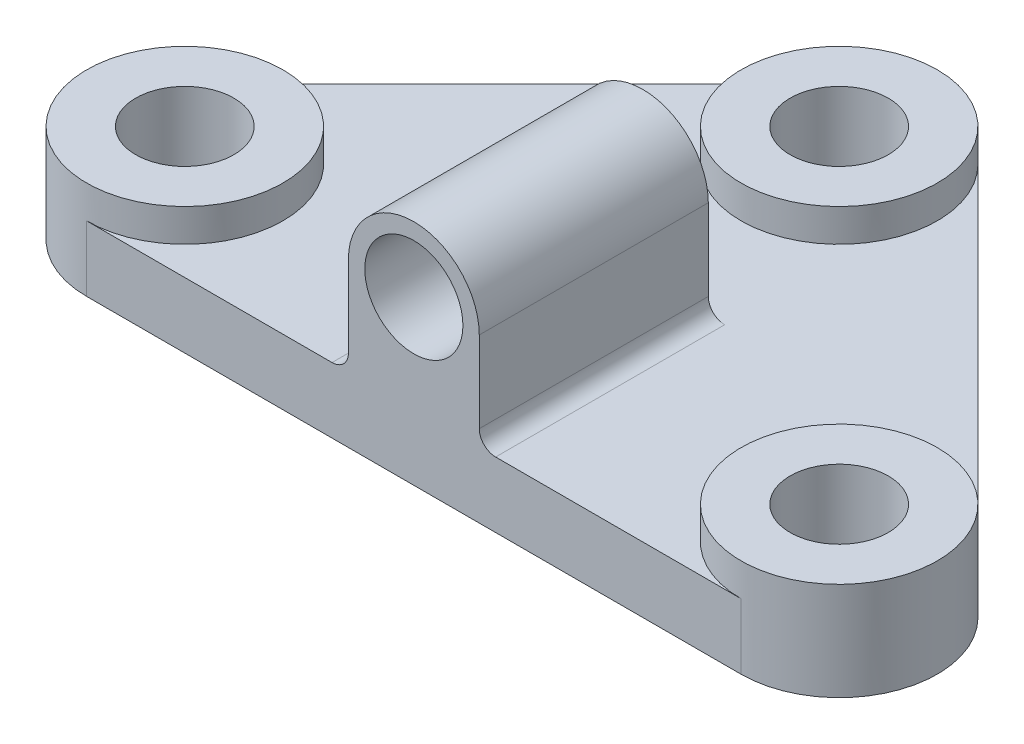
SolidWorks part; units mm, degrees
ref_plane "Front Plane" through (0, 0, 0) normal (0, 0, 1) x (1, 0, 0)
ref_plane "Top Plane" through (0, 0, 0) normal (0, 1, 0) x (1, 0, 0)
ref_plane "Right Plane" through (0, 0, 0) normal (1, 0, 0) x (0, 0, -1)
sketch "Sketch1" plane through (0, 0, 0) normal (0, 1, 0) x (1, 0, 0)
  line L0 (-100, 0) -> (100, 0) construction
  line L4 (-100, 0) -> (0, 100) construction
  line L5 (0, 100) -> (100, 0) construction
  line L6 (-121.2132, 21.2132) -> (-21.2132, 121.2132)
  line L7 (-100, -30) -> (100, -30)
  line L8 (21.2132, 121.2132) -> (121.2132, 21.2132)
  arc A1 (-21.2132, 121.2132) -> (21.2132, 121.2132) centre (0, 100) ccw
  arc A2 (-100, -30) -> (-121.2132, 21.2132) centre (-100, 0) ccw
  arc A3 (121.2132, 21.2132) -> (100, -30) centre (100, 0) ccw
  circle A4 centre (0, 100) radius 15
  circle A5 centre (-100, 0) radius 15
  circle A6 centre (100, 0) radius 15
  point P1 (0, 0)
  point P11 (0, 0)
  dimension "D3" = 60
  dimension "D4" = 60
  dimension "D5" = 60
  dimension "D6" = 30
  dimension "D7" = 30
  dimension "D8" = 30
  dimension "D1" = 200
  dimension "D2" = 100
extrude "Boss-Extrude2" add sketch "Sketch1" along normal blind 20 contours A3 L7 A2 L6 A1 L8
sketch "Sketch3" plane through (0, 0, 0) normal (0, -1, 0) x (1, 0, 0)
  circle A0 centre (0, -100) radius 30
  circle A1 centre (0, -100) radius 15
  circle A2 centre (100, 0) radius 15
  circle A3 centre (100, 0) radius 30
  circle A4 centre (-100, 0) radius 15
  circle A5 centre (-100, 0) radius 30
  dimension "D1" = 60
  dimension "D2" = 60
  dimension "D3" = 30
  dimension "D4" = 60
  dimension "D5" = 30
  dimension "D6" = 30
extrude "Boss-Extrude3" add sketch "Sketch3" against normal blind 30
sketch "Sketch5" plane through (0, 0, 30) normal (0, 0, 1) x (1, 0, 0)
  line L0 (0, 0) -> (0, 69.8) construction
  line L1 (-20, 49.8) -> (-20, 0)
  line L2 (15, 0) -> (-15, 0) construction
  line L3 (20, 49.8) -> (20, 0)
  line L4 (-100, 20) -> (100, 20) construction
  line L5 (-20, 0) -> (20, 0)
  circle A0 centre (0, 49.8) radius 15
  arc A1 (20, 49.8) -> (-20, 49.8) centre (0, 49.8) ccw
  dimension "D1" = 30
  dimension "D2" = 40
  dimension "D4" = 69.8
  dimension "D3" = 49.8
  dimension "D5" = 29.8
extrude "Boss-Extrude4" add sketch "Sketch5" against normal blind 70
fillet "Fillet1" radius 5 2 edges at (20, 20, -5) (-20, 20, -5)
